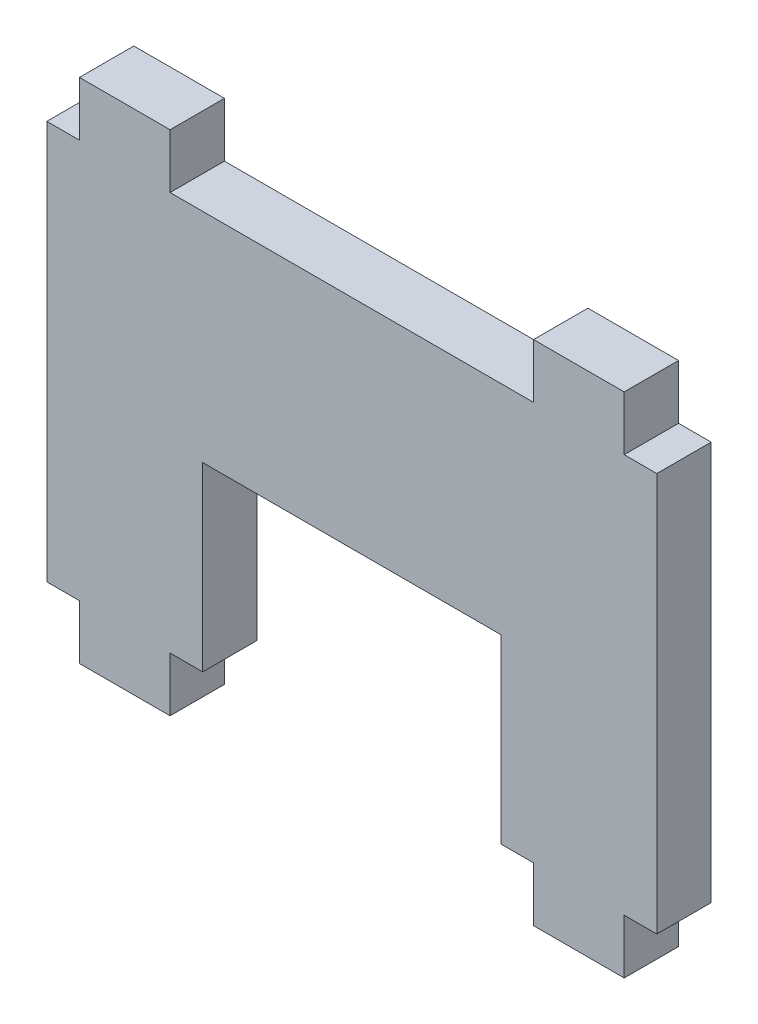
SolidWorks part; units mm, degrees
material "Balsa"
ref_plane "Alzado" through (0, 0, 0) normal (0, 0, 1) x (1, 0, 0)
ref_plane "Planta" through (0, 0, 0) normal (0, 1, 0) x (1, 0, 0)
ref_plane "Vista lateral" through (0, 0, 0) normal (1, 0, 0) x (0, 0, -1)
sketch "Croquis3" plane through (0, 0, 0) normal (0, 0, 1) x (1, 0, 0)
  line L0 (25.05, 0) -> (26.85, 0)
  line L1 (0, 0) -> (1.8, 0)
  line L2 (0, 0) -> (0, 22)
  line L3 (0, 22) -> (1.8, 22)
  line L4 (33.65, 0) -> (33.65, 22)
  line L7 (8.6, 10) -> (25.05, 10)
  line L8 (25.05, 0) -> (25.05, 10)
  line L9 (8.6, 10) -> (8.6, 0)
  line L10 (6.8, 0) -> (8.6, 0)
  line L12 (1.8, 0) -> (1.8, -3)
  line L13 (1.8, -3) -> (6.8, -3)
  line L14 (6.8, 0) -> (6.8, -3)
  line L16 (26.85, 0) -> (26.85, -3)
  line L17 (26.85, -3) -> (31.85, -3)
  line L18 (31.85, 0) -> (31.85, -3)
  line L19 (31.85, 0) -> (33.65, 0)
  line L21 (1.8, 22) -> (1.8, 25)
  line L22 (1.8, 25) -> (6.8, 25)
  line L23 (6.8, 22) -> (6.8, 25)
  line L25 (26.85, 22) -> (26.85, 25)
  line L26 (26.85, 25) -> (31.85, 25)
  line L27 (31.85, 22) -> (31.85, 25)
  line L28 (6.8, 22) -> (26.85, 22)
  line L29 (31.85, 22) -> (33.65, 22)
  dimension "D1" = 33.65
  dimension "D2" = 22
  dimension "D3" = 5
  dimension "D4" = 1.8
  dimension "D5" = 3
  dimension "D6" = 3
  dimension "D7" = 5
  dimension "D8" = 1.8
  dimension "D9" = 10
  dimension "D10" = 5
  dimension "D11" = 5
  dimension "D12" = 3
  dimension "D13" = 3
  dimension "D14" = 1.8
  dimension "D15" = 1.8
extrude "Saliente-Extruir1" add sketch "Croquis3" along normal blind 3
